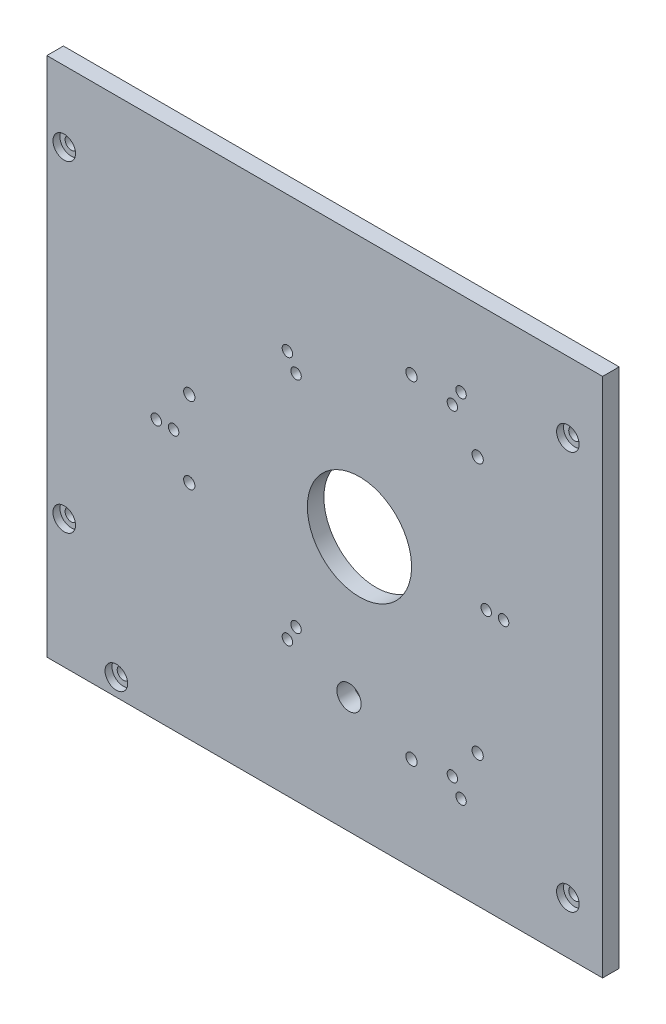
SolidWorks part; units mm, degrees
ref_plane "Front Plane" through (0, 0, 0) normal (0, 0, 1) x (1, 0, 0)
ref_plane "Top Plane" through (0, 0, 0) normal (0, 1, 0) x (1, 0, 0)
ref_plane "Right Plane" through (0, 0, 0) normal (1, 0, 0) x (0, 0, -1)
ref_plane "Plane1" through (0, 0, 4.76) normal (0, 0, 1) x (1, 0, 0)
sketch "Sketch1" plane through (0, 0, 4.76) normal (0, 0, 1) x (1, 0, 0)
  line L0 (70, 75) -> (-90, 75)
  line L1 (-90, 75) -> (-90, -75)
  line L2 (-90, -75) -> (70, -75)
  line L3 (70, -75) -> (70, 75)
extrude "Boss-Extrude1" add sketch "Sketch1" against normal blind 4.76
ref_plane "Plane2" through (0, 36.9352, 0) normal (0, 1, 0) x (1, 0, 0)
sketch "Sketch2" plane through (0, 36.9352, 0) normal (0, 1, 0) x (1, 0, 0)
  line L0 (35.6473, 0) -> (34.0263, 0)
  line L1 (34.0263, 0) -> (34.0263, -4.76)
  line L2 (34.0263, -4.76) -> (35.6473, -4.76)
  line L3 (35.6473, -4.76) -> (35.6473, -2.76)
  line L4 (35.6473, -2.76) -> (35.6473, 0)
  line L5 (34.0263, 0) -> (34.0263, -4.76) construction
revolve "Cut-Revolve1" cut sketch "Sketch2" angle 360 about L5
ref_plane "Plane3" through (0, 11, 0) normal (0, 1, 0) x (1, 0, 0)
sketch "Sketch3" plane through (0, 11, 0) normal (0, 1, 0) x (1, 0, 0)
  line L0 (-47.379, 0) -> (-49, 0)
  line L1 (-49, 0) -> (-49, -4.76)
  line L2 (-49, -4.76) -> (-47.379, -4.76)
  line L3 (-47.379, -4.76) -> (-47.379, -2.76)
  line L4 (-47.379, -2.76) -> (-47.379, 0)
  line L5 (-49, 0) -> (-49, -4.76) construction
revolve "Cut-Revolve2" cut sketch "Sketch3" angle 360 about L5
ref_plane "Plane4" through (0, -36.9352, 0) normal (0, 1, 0) x (1, 0, 0)
sketch "Sketch4" plane through (0, -36.9352, 0) normal (0, 1, 0) x (1, 0, 0)
  line L0 (35.6473, 0) -> (34.0263, 0)
  line L1 (34.0263, 0) -> (34.0263, -4.76)
  line L2 (34.0263, -4.76) -> (35.6473, -4.76)
  line L3 (35.6473, -4.76) -> (35.6473, -2.76)
  line L4 (35.6473, -2.76) -> (35.6473, 0)
  line L5 (34.0263, 0) -> (34.0263, -4.76) construction
revolve "Cut-Revolve3" cut sketch "Sketch4" angle 360 about L5
ref_plane "Plane5" through (0, -47.9352, 0) normal (0, 1, 0) x (1, 0, 0)
sketch "Sketch5" plane through (0, -47.9352, 0) normal (0, 1, 0) x (1, 0, 0)
  line L0 (16.5947, 0) -> (14.9737, 0)
  line L1 (14.9737, 0) -> (14.9737, -4.76)
  line L2 (14.9737, -4.76) -> (16.5947, -4.76)
  line L3 (16.5947, -4.76) -> (16.5947, -2.76)
  line L4 (16.5947, -2.76) -> (16.5947, 0)
  line L5 (14.9737, 0) -> (14.9737, -4.76) construction
revolve "Cut-Revolve4" cut sketch "Sketch5" angle 360 about L5
ref_plane "Plane6" through (0, 47.9352, 0) normal (0, 1, 0) x (1, 0, 0)
sketch "Sketch6" plane through (0, 47.9352, 0) normal (0, 1, 0) x (1, 0, 0)
  line L0 (16.5947, 0) -> (14.9737, 0)
  line L1 (14.9737, 0) -> (14.9737, -4.76)
  line L2 (14.9737, -4.76) -> (16.5947, -4.76)
  line L3 (16.5947, -4.76) -> (16.5947, -2.76)
  line L4 (16.5947, -2.76) -> (16.5947, 0)
  line L5 (14.9737, 0) -> (14.9737, -4.76) construction
revolve "Cut-Revolve5" cut sketch "Sketch6" angle 360 about L5
ref_plane "Plane7" through (0, -11, 0) normal (0, 1, 0) x (1, 0, 0)
sketch "Sketch7" plane through (0, -11, 0) normal (0, 1, 0) x (1, 0, 0)
  line L0 (-47.379, 0) -> (-49, 0)
  line L1 (-49, 0) -> (-49, -4.76)
  line L2 (-49, -4.76) -> (-47.379, -4.76)
  line L3 (-47.379, -4.76) -> (-47.379, -2.76)
  line L4 (-47.379, -2.76) -> (-47.379, 0)
  line L5 (-49, 0) -> (-49, -4.76) construction
revolve "Cut-Revolve6" cut sketch "Sketch7" angle 360 about L5
hole_wizard "Ø7.0 (7) Diameter Hole1" positions "Sketch9" profile "Sketch8" hole size "Ø7.0" standard "ANSI Metric"
sketch "Sketch9" plane through (0, 0, 0) normal (0, 0, -1) x (-1, 0, 0)
  point P0 (3, -41.5)
sketch "Sketch8" plane through (-3, -41.5, 0) normal (1, 0, 0) x (0, 1, 0)
  line L0 (0, 0) -> (0, 4.76)
  line L1 (0, 4.76) -> (3.5, 4.76)
  line L2 (3.5, 4.76) -> (3.5, 0)
  line L5 (3.5, 0) -> (0, 0)
  line L11 (0, -6.35) -> (0, 107.95) construction
  dimension "Thru Hole Dia." = 7
  dimension "Thru Hole Depth" = 4.76
hole_wizard "CBORE for M3 Hex Head Machine Screw1" positions "Sketch11" profile "Sketch10" counterbore size "M3" standard "ANSI Metric"
sketch "Sketch11" plane through (0, 0, 4.76) normal (0, 0, 1) x (1, 0, 0)
  point P0 (-70, -70)
  point P1 (60, -60)
  point P2 (-85, 54.6672)
  point P3 (60, 54.6672)
  point P4 (-85, -38)
sketch "Sketch10" plane through (-70, -70, 4.76) normal (1, 0, 0) x (0, -1, 0)
  line L0 (0, 0) -> (0, 4.76)
  line L1 (0, 4.76) -> (1.75, 4.76)
  line L3 (1.75, 4.76) -> (1.75, 2)
  line L4 (1.75, 2) -> (3.25, 2)
  line L5 (3.25, 2) -> (3.25, 0)
  line L7 (3.25, 0) -> (0, 0)
  line L11 (0, -6.35) -> (0, 107.95) construction
  dimension "Thru Hole Dia." = 3.5
  dimension "Thru Hole Depth" = 4.76
  dimension "C'Bore Dia." = 6.5
  dimension "C'Bore Depth" = 2
hole_wizard "Ø3.0 (3) Diameter Hole1" positions "Sketch13" profile "Sketch12" hole size "Ø3.0" standard "ANSI Metric"
sketch "Sketch13" plane through (0, 0, 0) normal (0, 0, -1) x (-1, 0, 0)
  point P0 (20.75, 35.9401)
  point P1 (18.25, 31.6099)
  point P2 (20.75, -35.9401)
  point P3 (18.25, -31.6099)
  point P4 (-41.5, 0)
  point P5 (-29.25, 50.6625)
  point P6 (-26.75, 46.3324)
  point P7 (-36.5, 0)
  point P8 (58.5, 0)
  point P9 (53.5, 0)
  point P10 (-26.75, -46.3324)
  point P11 (-29.25, -50.6625)
sketch "Sketch12" plane through (-20.75, 35.9401, 0) normal (1, 0, 0) x (0, 1, 0)
  line L0 (0, 0) -> (0, 4.76)
  line L1 (0, 4.76) -> (1.5, 4.76)
  line L2 (1.5, 4.76) -> (1.5, 0)
  line L5 (1.5, 0) -> (0, 0)
  line L11 (0, -6.35) -> (0, 107.95) construction
  dimension "Thru Hole Dia." = 3
  dimension "Thru Hole Depth" = 4.76
hole_wizard "M27 Clearance Hole1" positions "Sketch15" profile "Sketch14" hole size "M27" standard "ANSI Metric"
sketch "Sketch15" plane through (0, 0, 0) normal (0, 0, -1) x (-1, 0, 0)
  point P0 (0, 0)
sketch "Sketch14" plane through (0, 0, 0) normal (1, 0, 0) x (0, 1, 0)
  line L0 (0, 0) -> (0, 4.76)
  line L1 (0, 4.76) -> (15, 4.76)
  line L2 (15, 4.76) -> (15, 0)
  line L5 (15, 0) -> (0, 0)
  line L11 (0, -6.35) -> (0, 107.95) construction
  dimension "Thru Hole Dia." = 30
  dimension "Thru Hole Depth" = 4.76
